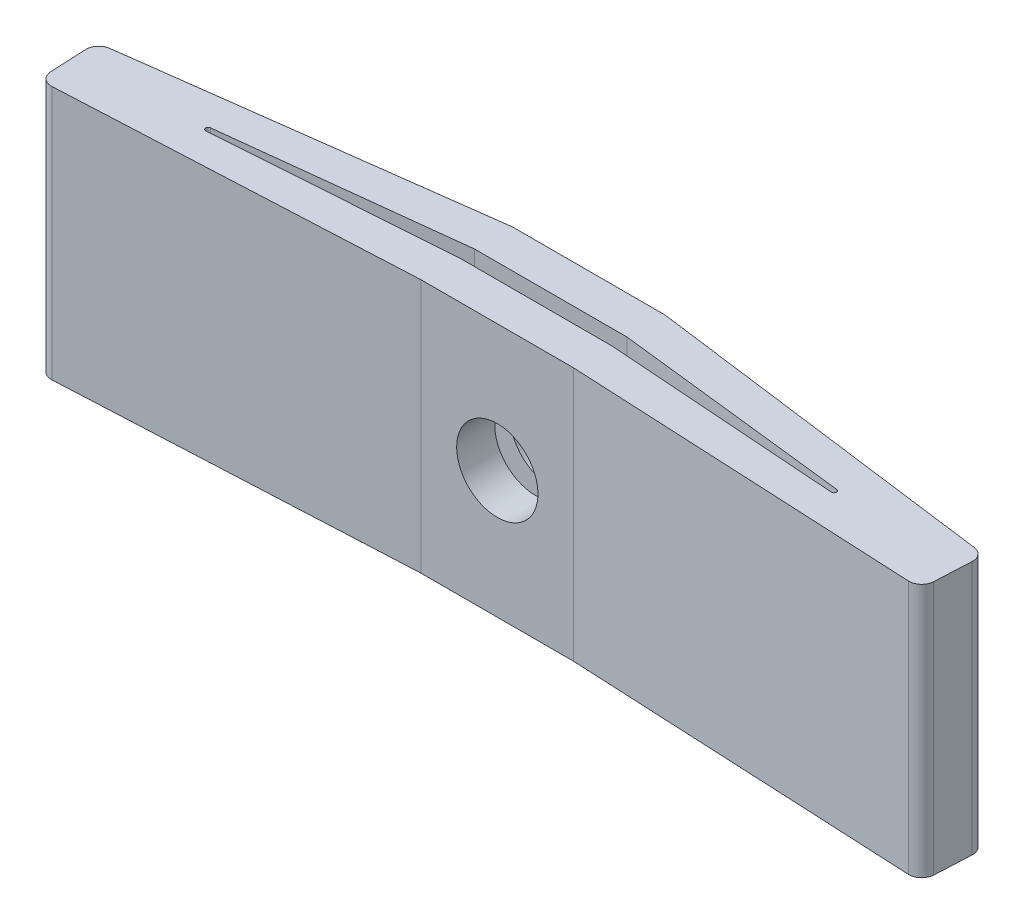
SolidWorks part; units mm, degrees
ref_plane "Front" through (0, 0, 0) normal (0, 0, 1) x (1, 0, 0)
ref_plane "Top" through (0, 0, 0) normal (0, 1, 0) x (1, 0, 0)
ref_plane "Right" through (0, 0, 0) normal (1, 0, 0) x (0, 0, -1)
sketch "Sketch1" plane through (0, 0, 0) normal (0, 1, 0) x (1, 0, 0)
  line L0 (0, 0) -> (34.7, 0) construction
  line L1 (17.35, 0) -> (17.35, 17.8266) construction
  line L2 (20.35, 0.7) -> (14.35, 0.7)
  line L3 (14.35, 0.7) -> (0, 0)
  line L4 (0, 0) -> (-0.1171, 2.4)
  line L5 (20.35, 2.2) -> (14.35, 2.2)
  line L6 (14.35, 2.2) -> (0.35, 1.2)
  line L7 (0.35, 1.2) -> (14.35, 2.8)
  line L8 (14.35, 2.8) -> (20.35, 2.8)
  line L9 (20.35, 4.3) -> (34.8171, 2.4)
  line L10 (20.35, 4.3) -> (14.35, 4.3)
  line L11 (14.35, 4.3) -> (-0.1171, 2.4)
  line L12 (34.35, 1.2) -> (20.35, 2.8)
  line L13 (20.35, 2.2) -> (34.35, 1.2)
  line L14 (34.7, 0) -> (34.8171, 2.4)
  line L15 (20.35, 0.7) -> (34.7, 0)
  line L16 (14.35, 4.3) -> (14.35, 0.7) construction
  point P25 (17.35, 4.3)
  point P26 (17.35, 2.8)
  point P28 (17.35, 2.2)
  point P29 (17.35, 0.7)
  dimension "D1" = 34.7
  dimension "D2" = 1.4
  dimension "D3" = 1.5
  dimension "D4" = 1.5
  dimension "D5" = 0.6
  dimension "D6" = 6
  dimension "D7" = 17
  dimension "D8" = 2.4
  dimension "D9" = 1.2
extrude "Boss-Extrude1" add sketch "Sketch1" along normal blind 10
fillet "Fillet1" radius 0.1 2 edges at (34.35, 5, -1.2) (0.35, 5, -1.2)
fillet "Fillet2" radius 0.5 4 edges at (-0.1171, 5, -2.4) (34.8171, 5, -2.4) (34.7, 5, 0) (0, 5, 0)
sketch "Sketch2" plane through (0, 0, -4.3) normal (0, 0, -1) x (-1, 0, 0)
  line L0 (-17.35, 5) -> (-17.35, 0) construction
  line L1 (-20.35, 0) -> (-14.35, 0) construction
  line L2 (-17.35, 5) -> (-17.35, 10) construction
  line L3 (-20.35, 10) -> (-14.35, 10) construction
  circle A0 centre (-17.35, 5) radius 1.6
  dimension "D1" = 3.2
extrude "Cut-Extrude1" cut sketch "Sketch2" against normal through all
sketch "Sketch3" plane through (0.9002, 0, -6.8544) normal (0.1302, 0, -0.9915) x (-0.9915, 0, -0.1302)
  line L0 (-33.7475, 1) -> (-19.6168, 1) construction
  line L1 (-33.7475, 10) -> (-33.7475, 0) construction
  line L2 (-19.6168, 10) -> (-19.6168, 0) construction
  line L4 (-33.7475, 0) -> (-19.6168, 0) construction
  text T0 "BCL" font "Century Gothic" height in points 20
  dimension "D1" = 1
extrude "Boss-Extrude2" [suppressed] add sketch "Sketch3" along normal blind 0.4
sketch "Sketch4" plane through (-0.3118, 0, -2.3744) normal (-0.1302, 0, -0.9915) x (-0.9915, 0, 0.1302)
  line L0 (-14.7877, 1) -> (-0.6571, 1) construction
  line L1 (-14.7877, 10) -> (-14.7877, 0) construction
  line L2 (-0.6571, 0) -> (-0.6571, 10) construction
  line L3 (-14.7877, 0) -> (-0.6571, 0) construction
  text T0 "02" font "Century Gothic" height in points 20
  dimension "D1" = 1
extrude "Boss-Extrude3" [suppressed] add sketch "Sketch4" along normal blind 0.4
sketch "Sketch5" plane through (-0.3118, 0, -2.3744) normal (-0.1302, 0, -0.9915) x (-0.9915, 0, 0.1302)
  line L0 (-14.7877, 1) -> (-0.6571, 1) construction
  line L1 (-14.7877, 10) -> (-14.7877, 0) construction
  line L2 (-0.6571, 0) -> (-0.6571, 10) construction
  line L3 (-14.7877, 0) -> (-0.6571, 0) construction
  text T0 "..."
  dimension "D1" = 1
extrude "revision indication" add sketch "Sketch5" along normal blind 0.4
